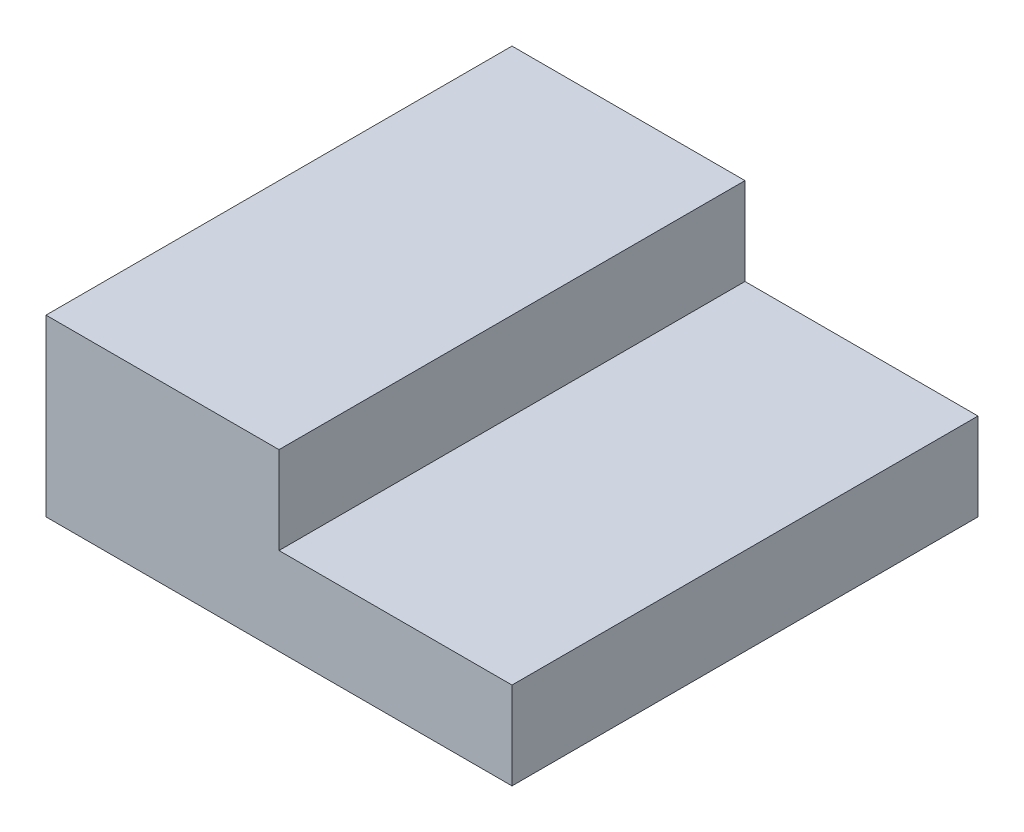
SolidWorks part; units mm, degrees
ref_plane "Front Plane" through (0, 0, 0) normal (0, 0, 1) x (1, 0, 0)
ref_plane "Top Plane" through (0, 0, 0) normal (0, 1, 0) x (1, 0, 0)
ref_plane "Right Plane" through (0, 0, 0) normal (1, 0, 0) x (0, 0, -1)
sketch "Sketch1" plane through (0, 0, 0) normal (0, 0, 1) x (1, 0, 0)
  line L0 (0, 0) -> (609.6, 0)
  line L1 (609.6, 0) -> (609.6, 114.3)
  line L2 (609.6, 114.3) -> (304.8, 114.3)
  line L3 (304.8, 114.3) -> (304.8, 228.6)
  line L4 (304.8, 228.6) -> (0, 228.6)
  line L5 (0, 228.6) -> (0, 0)
  dimension "D1" = 304.8
  dimension "D2" = 609.6
  dimension "D3" = 228.6
  dimension "D4" = 114.3
extrude "Boss-Extrude1" add sketch "Sketch1" against normal blind 609.6
